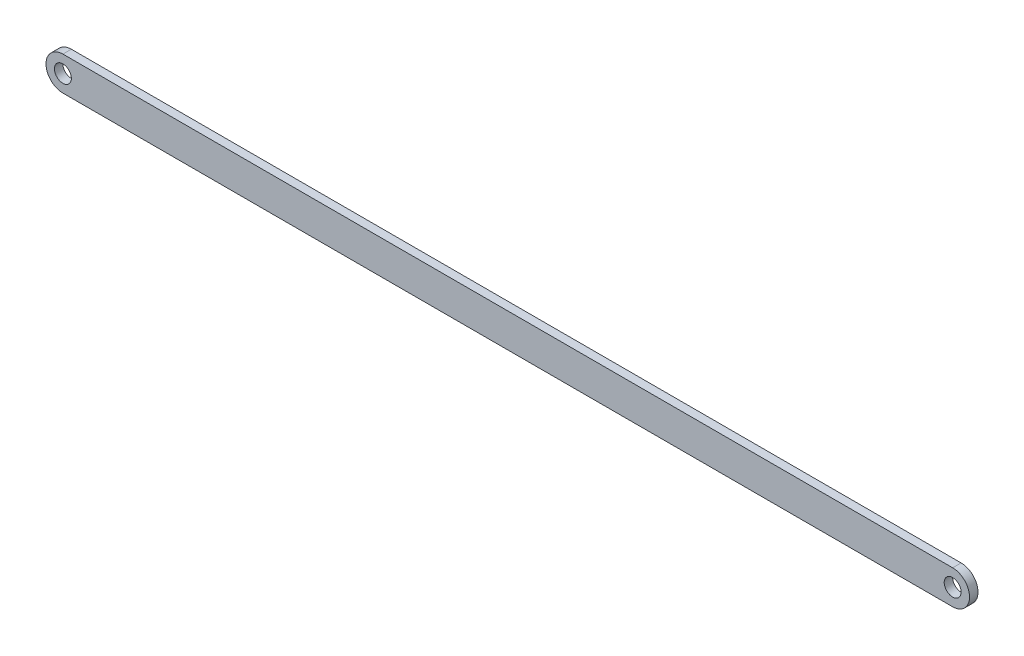
SolidWorks part; units mm, degrees
ref_plane "Plano frontal" through (0, 0, 0) normal (0, 0, 1) x (1, 0, 0)
ref_plane "Plano superior" through (0, 0, 0) normal (0, 1, 0) x (1, 0, 0)
ref_plane "Plano direito" through (0, 0, 0) normal (1, 0, 0) x (0, 0, -1)
sketch "Esboço1" plane through (0, 0, 0) normal (0, 0, 1) x (1, 0, 0)
  line L0 (-52.66, 2) -> (52.66, 2)
  line L1 (-52.66, 0) -> (52.66, 0) construction
  line L2 (-52.66, -2) -> (52.66, -2)
  arc A0 (-52.66, 2) -> (-52.66, -2) centre (-52.66, 0) ccw
  arc A1 (52.66, 2) -> (52.66, -2) centre (52.66, 0) cw
  circle A2 centre (-52.66, 0) radius 1
  circle A3 centre (52.66, 0) radius 1
  point P3 (0, 2)
  dimension "D1" = 105.32
  dimension "D2" = 2
extrude "Ressalto-extrusão1" add sketch "Esboço1" along normal blind 1
